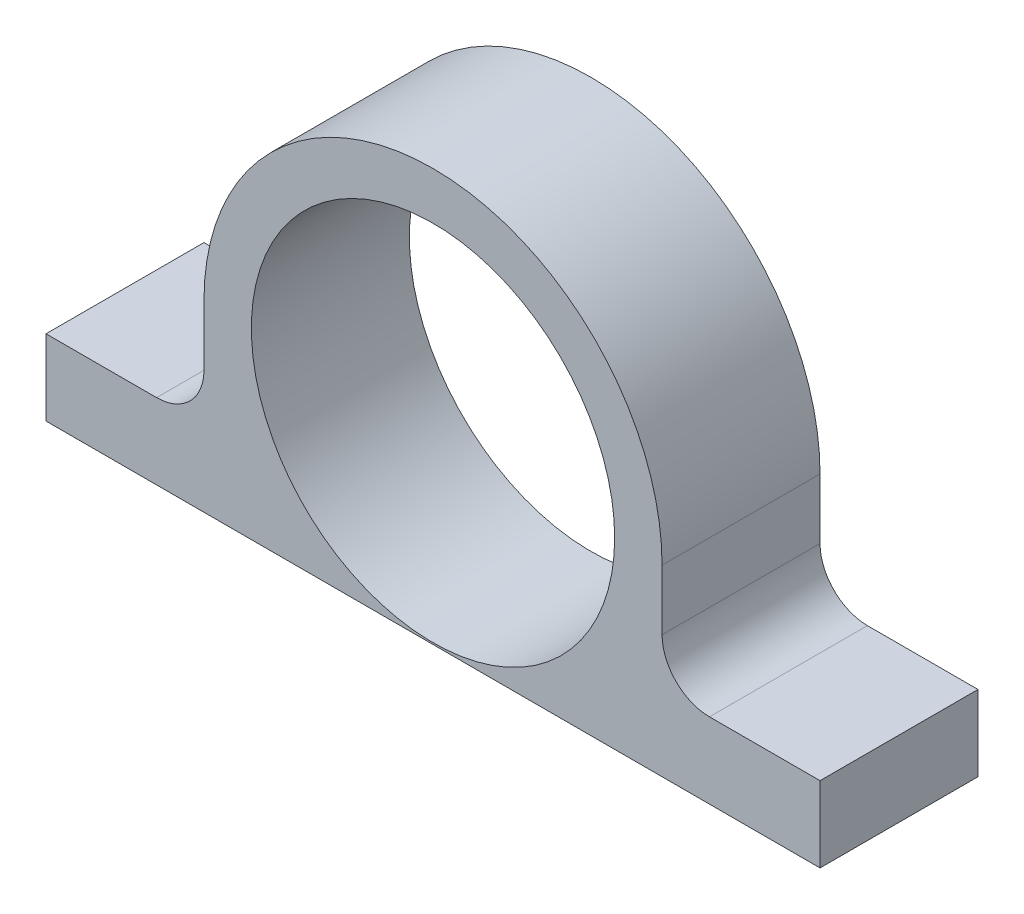
SolidWorks part; units mm, degrees
ref_plane "Front Plane" through (0, 0, 0) normal (0, 0, 1) x (1, 0, 0)
ref_plane "Top Plane" through (0, 0, 0) normal (0, 1, 0) x (1, 0, 0)
ref_plane "Right Plane" through (0, 0, 0) normal (1, 0, 0) x (0, 0, -1)
sketch "Sketch1" plane through (0, 0, 0) normal (0, 0, 1) x (1, 0, 0)
  line L0 (-11.5, 84.8872) -> (-11.5, 78.0733) construction
  line L1 (-14.5, 75.0733) -> (-21.5, 75.0733) construction
  line L2 (-21.5, 75.0733) -> (-21.5, 73.2872) construction
  line L4 (-21.5, 73.2872) -> (0, 73.2872) construction
  line L5 (0, 84.8872) -> (0, 96.3872) construction
  line L6 (11.5, 84.8872) -> (11.5, 78.0733) construction
  line L7 (14.5, 75.0733) -> (21.5, 75.0733) construction
  line L8 (21.5, 75.0733) -> (21.5, 73.2872) construction
  line L9 (21.5, 73.2872) -> (0, 73.2872) construction
  line L10 (-14.5, 84.8872) -> (-14.5, 81.0733)
  line L11 (-17.5, 78.0733) -> (-24.5, 78.0733)
  line L12 (-24.5, 78.0733) -> (-24.5, 73.2872)
  line L13 (14.5, 84.8872) -> (14.5, 81.0733)
  line L14 (17.5, 78.0733) -> (24.5, 78.0733)
  line L15 (24.5, 78.0733) -> (24.5, 73.2872)
  line L16 (-24.5, 73.2872) -> (24.5, 73.2872)
  line L17 (14.5, 78.0733) -> (24.5, 78.0733) construction
  line L18 (14.5, 84.8872) -> (14.5, 78.0733) construction
  line L19 (-14.5, 78.0733) -> (-24.5, 78.0733) construction
  line L20 (-14.5, 84.8872) -> (-14.5, 78.0733) construction
  arc A1 (11.5, 84.8872) -> (-11.5, 84.8872) centre (0, 84.8872) ccw
  arc A2 (-11.5, 78.0733) -> (-14.5, 75.0733) centre (-14.5, 78.0733) cw construction
  arc A3 (11.5, 78.0733) -> (14.5, 75.0733) centre (14.5, 78.0733) ccw construction
  arc A4 (14.5, 84.8872) -> (-14.5, 84.8872) centre (0, 84.8872) ccw
  arc A6 (-17.5, 78.0733) -> (-14.5, 81.0733) centre (-17.5, 81.0733) ccw
  arc A7 (11.5, 84.8872) -> (-11.5, 84.8872) centre (0, 84.8872) cw
  arc A8 (17.5, 78.0733) -> (14.5, 81.0733) centre (17.5, 81.0733) cw
  arc A9 (14.5, 78.0733) -> (14.5, 78.0733) centre (14.5, 78.0733) ccw construction
  arc A10 (-14.5, 78.0733) -> (-14.5, 78.0733) centre (-14.5, 78.0733) cw construction
  dimension "D1" = 3
  dimension "D6" = 3
  dimension "D2" = 10
  dimension "D3" = 4.786
  dimension "D4" = 3
  dimension "D5" = 3
extrude "Boss-Extrude1" add sketch "Sketch1" along normal blind 10 contours L14 A8 L13 A4 L10 A6 L11 L12 L16 L15 A1 A7
